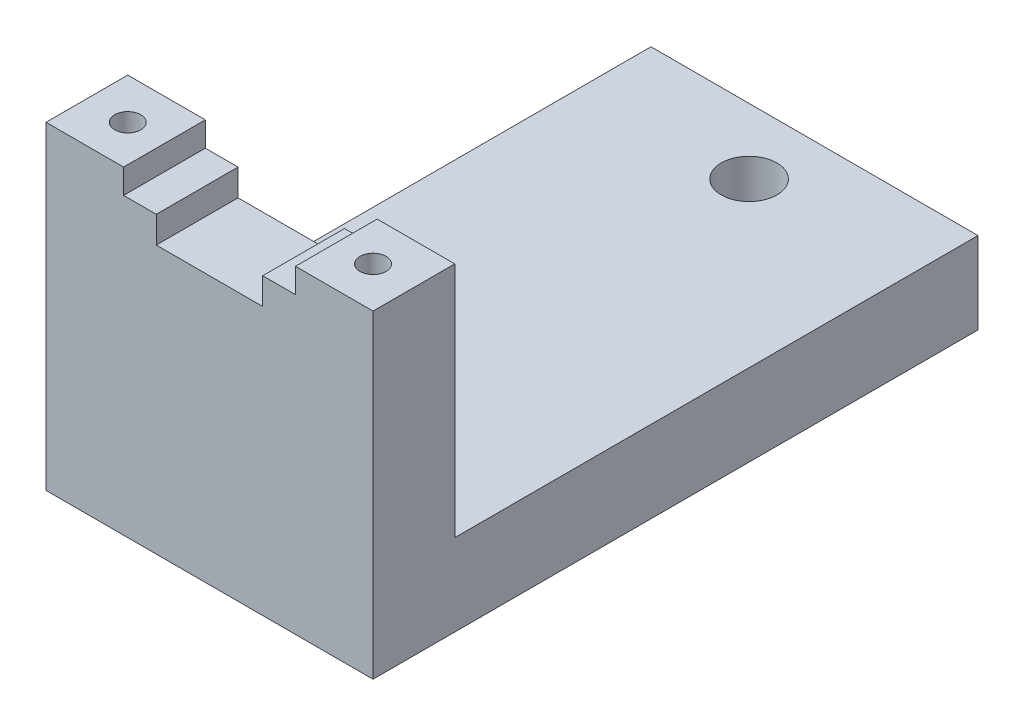
SolidWorks part; units mm, degrees
ref_plane "Front Plane" through (0, 0, 0) normal (0, 0, 1) x (1, 0, 0)
ref_plane "Top Plane" through (0, 0, 0) normal (0, 1, 0) x (1, 0, 0)
ref_plane "Right Plane" through (0, 0, 0) normal (1, 0, 0) x (0, 0, -1)
sketch "Sketch2" plane through (0, 0, 0) normal (0, 1, 0) x (1, 0, 0)
  line L1 (-10, -18.5) -> (10, -18.5)
  line L2 (-10, -18.5) -> (-10, 18.5)
  line L3 (-10, 18.5) -> (10, 18.5)
  line L4 (10, -18.5) -> (10, 18.5)
  line L5 (-10, -18.5) -> (10, 18.5) construction
  line L6 (-10, 18.5) -> (10, -18.5) construction
  point P0 (0, 0)
  dimension "D1" = 20
  dimension "D2" = 37
extrude "Extrude1" add sketch "Sketch2" along normal blind 5
sketch "Sketch3" plane through (0, 0, 0) normal (0, -1, 0) x (1, 0, 0)
  line L0 (0, -22.2607) -> (0, 26.2443) construction
hole_wizard "Ø3.4 (3.4) Diameter Hole1" positions "3DSketch1" profile "Sketch4" hole size "Ø3.4" standard "Ansi Metric" end condition through all
sketch3d "3DSketch1"
  line L0 (0, 0, -22.2607) -> (0, 0, 26.2443) construction
  line L1 (10, 0, -18.5) -> (-10, 0, -18.5) construction
  point P0 (0, 0, -14.5)
  dimension "D1" = 4
sketch "Sketch4" plane through (0, 0, -14.5) normal (1, 0, 0) x (0, 0, -1)
  line L0 (0, 0) -> (0, 5)
  line L1 (0, 5) -> (1.7, 5)
  line L2 (1.7, 5) -> (1.7, 0)
  line L5 (1.7, 0) -> (0, 0)
  line L11 (0, -6.35) -> (0, 107.95) construction
  dimension "Thru Hole Dia." = 3.4
  dimension "Thru Hole Depth" = 5
pattern_linear "LPattern1" count 2 spacing 22.9 along (0, 0, 1) of "Ø3.4 (3.4) Diameter Hole1"
sketch "Sketch5" plane through (0, 5, 0) normal (0, 1, 0) x (1, 0, 0)
  line L0 (10, -18.5) -> (10, 18.5) construction
  line L1 (-10, -18.5) -> (10, -18.5)
  line L2 (-10, -18.5) -> (-10, -13.5)
  line L3 (-10, -13.5) -> (10, -13.5)
  line L4 (10, -18.5) -> (10, -13.5)
  dimension "D1" = 5
extrude "Extrude2" add sketch "Sketch5" along normal blind 14.5
sketch "Sketch9" plane through (0, 19.5, 0) normal (0, 1, 0) x (-1, 0, 0)
  line L0 (0, 21.1862) -> (0, 8.9514) construction
  line L1 (12.1331, 16) -> (-12.1307, 16) construction
hole_wizard "M2x0.4 Tapped Hole1" positions "3DSketch3" profile "Sketch10" tap size "M2x0.4" standard "Ansi Metric"
sketch3d "3DSketch3"
  line L0 (-12.1331, 19.5, 16) -> (12.1307, 19.5, 16) construction
  line L1 (0, 19.5, 21.1862) -> (0, 19.5, 8.9514) construction
  point P0 (-7.5, 19.5, 16)
  dimension "D1" = 7.5
sketch "Sketch10" plane through (-7.5, 19.5, 16) normal (1, 0, 0) x (0, 0, 1)
  line L0 (0, 0) -> (0, 8.6807)
  line L1 (0, 8.6807) -> (0.8, 8.2)
  line L2 (0.8, 8.2) -> (0.8, 0)
  line L5 (0.8, 0) -> (0, 0)
  line L10 (0, 8.6807) -> (-0.8, 8.2) construction
  line L11 (0, -6.35) -> (0, 107.95) construction
  dimension "Tap Drill Dia." = 1.6
  dimension "Tap Drill Depth" = 8.2
  dimension "Drill Angle" = 118
pattern_linear "LPattern2" count 2 spacing 15 along (1, 0, 0) of "M2x0.4 Tapped Hole1"
sketch "Sketch6" plane through (0, 19.5, 0) normal (0, 1, 0) x (-1, 0, 0)
  line L0 (8.989, 16) -> (-10.2858, 16) construction
  line L1 (0, 20.0224) -> (0, 11.5445) construction
  line L2 (-10, 13.5) -> (10, 13.5) construction
  line L3 (5.255, 18.5) -> (-5.255, 18.5)
  line L4 (5.255, 18.5) -> (5.255, 13.5)
  line L5 (5.255, 13.5) -> (-5.255, 13.5)
  line L6 (-5.255, 18.5) -> (-5.255, 13.5)
  line L7 (5.255, 18.5) -> (-5.255, 13.5) construction
  line L8 (5.255, 13.5) -> (-5.255, 18.5) construction
  point P5 (0, 16)
  dimension "D1" = 10.51
extrude "Extrude3" cut sketch "Sketch6" against normal blind 1.5
sketch "Sketch7" plane through (0, 18, 0) normal (0, 1, 0) x (-1, 0, 0)
  line L0 (7.4352, 16) -> (-8.1481, 16) construction
  line L1 (0, 19.8046) -> (0, 11.9624) construction
  line L2 (-10, 13.5) -> (10, 13.5) construction
  line L3 (3.255, 18.5) -> (-3.255, 18.5)
  line L4 (3.255, 18.5) -> (3.255, 13.5)
  line L5 (3.255, 13.5) -> (-3.255, 13.5)
  line L6 (-3.255, 18.5) -> (-3.255, 13.5)
  line L7 (3.255, 18.5) -> (-3.255, 13.5) construction
  line L8 (3.255, 13.5) -> (-3.255, 18.5) construction
  point P5 (0, 16)
  dimension "D1" = 6.51
extrude "Extrude4" cut sketch "Sketch7" against normal blind 1.63
